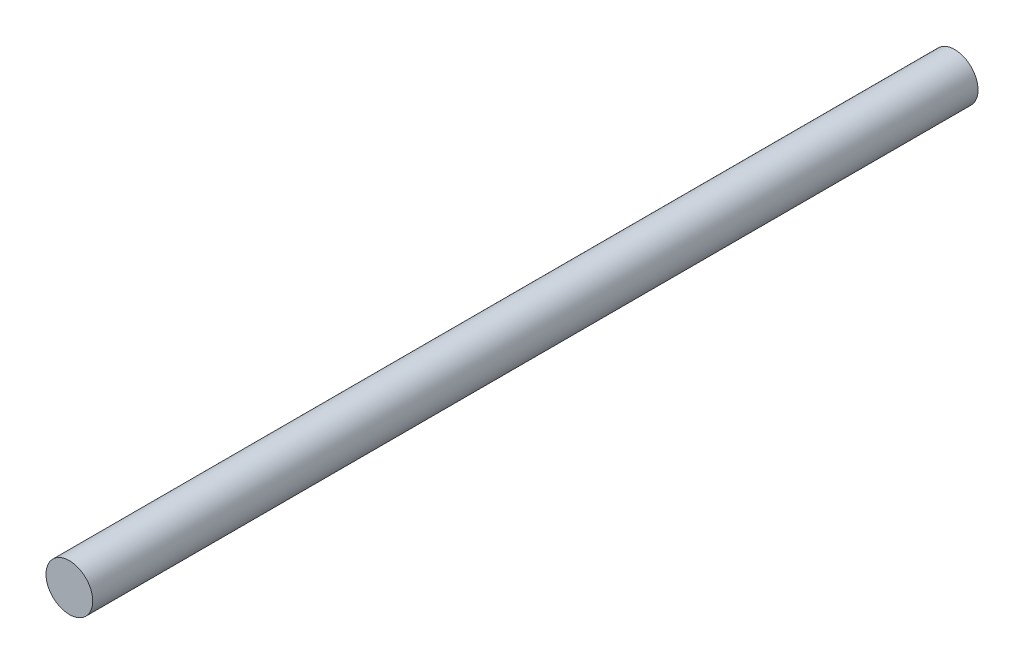
SolidWorks part; units mm, degrees
ref_plane "Front Plane" through (0, 0, 0) normal (0, 0, 1) x (1, 0, 0)
ref_plane "Top Plane" through (0, 0, 0) normal (0, 1, 0) x (1, 0, 0)
ref_plane "Right Plane" through (0, 0, 0) normal (1, 0, 0) x (0, 0, -1)
sketch "Sketch1" plane through (0, 0, 0) normal (0, 0, 1) x (1, 0, 0)
  circle A0 centre (0, 0) radius 3
  dimension "D1" = 6
extrude "Boss-Extrude1" add sketch "Sketch1" along normal blind 113.7
